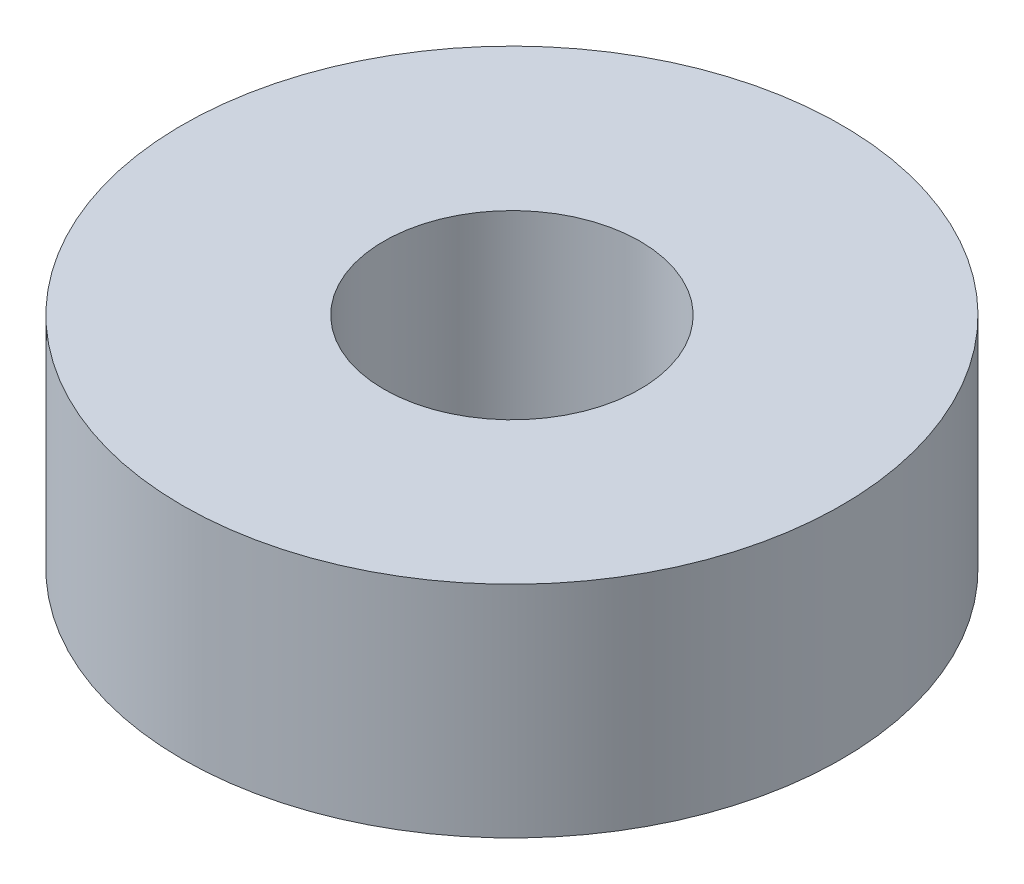
SolidWorks part; units mm, degrees
ref_plane "Спереди" through (0, 0, 0) normal (0, 0, 1) x (1, 0, 0)
ref_plane "Сверху" through (0, 0, 0) normal (0, 1, 0) x (1, 0, 0)
ref_plane "Справа" through (0, 0, 0) normal (1, 0, 0) x (0, 0, -1)
sketch "Эскиз1" plane through (0, 0, 0) normal (0, 1, 0) x (1, 0, 0)
  circle A0 centre (0, -2.2937) radius 9
  circle A1 centre (0, -2.2937) radius 3.5
extrude "Вытянуть1" add sketch "Эскиз1" along normal blind 6
